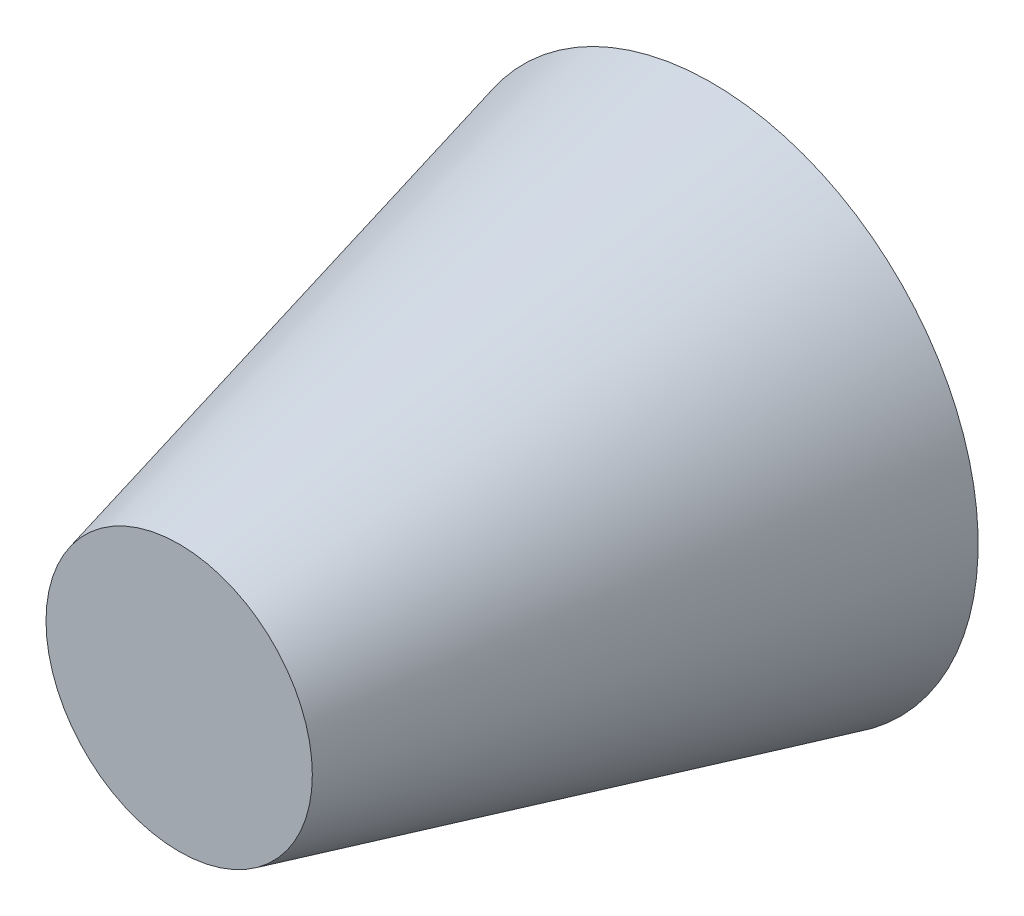
SolidWorks part; units mm, degrees
ref_plane "Front Plane" through (0, 0, 0) normal (0, 0, 1) x (1, 0, 0)
ref_plane "Top Plane" through (0, 0, 0) normal (0, 1, 0) x (1, 0, 0)
ref_plane "Right Plane" through (0, 0, 0) normal (1, 0, 0) x (0, 0, -1)
ref_plane "plane:profile-xz" through (0, 0, 0) normal (0, -1, 0) x (1, 0, 0)
sketch "sketch:main-profile" plane through (0, 0, 0) normal (0, -1, 0) x (1, 0, 0)
  line L0 (0, 0) -> (10, 0)
  line L1 (10, 0) -> (5, 20)
  line L2 (5, 20) -> (0, 20)
  line L3 (0, 20) -> (0, 0)
  line L4 (0, -5) -> (0, 25) construction
revolve "feature:frustum" add sketch "sketch:main-profile" angle 360 about L4
